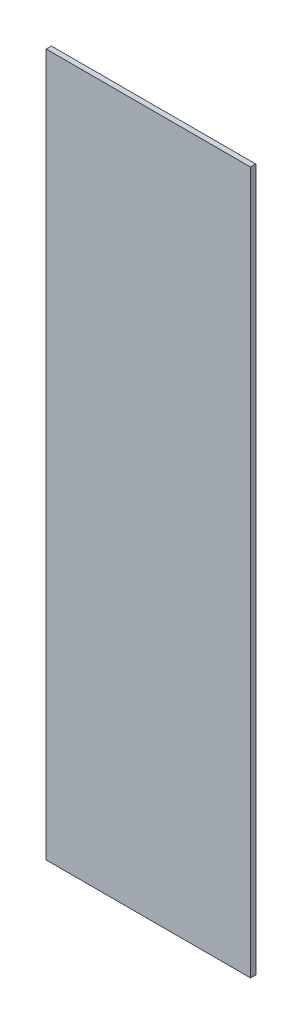
SolidWorks part; units mm, degrees
ref_plane "Plan de face" through (0, 0, 0) normal (0, 0, 1) x (1, 0, 0)
ref_plane "Plan de dessus" through (0, 0, 0) normal (0, 1, 0) x (1, 0, 0)
ref_plane "Plan de droite" through (0, 0, 0) normal (1, 0, 0) x (0, 0, -1)
sketch "Esquisse1" plane through (0, 0, 0) normal (0, 0, 1) x (1, 0, 0)
  line L1 (-97.5, 335) -> (97.5, 335)
  line L2 (-97.5, 335) -> (-97.5, -335)
  line L3 (-97.5, -335) -> (97.5, -335)
  line L4 (97.5, 335) -> (97.5, -335)
  line L5 (-97.5, 335) -> (97.5, -335) construction
  line L6 (-97.5, -335) -> (97.5, 335) construction
  point P0 (0, 0)
  dimension "D1" = 195
  dimension "D2" = 670
extrude "Boss.-Extru.1" add sketch "Esquisse1" along normal blind 5
